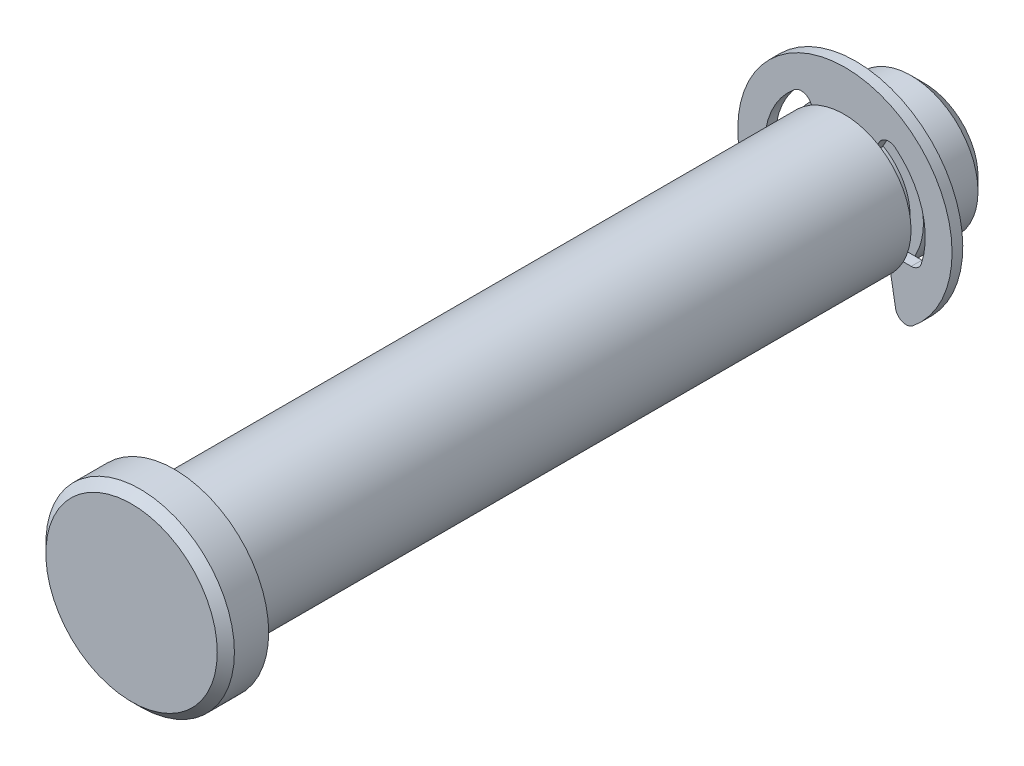
SolidWorks part; units mm, degrees
ref_plane "Front" through (0, 0, 0) normal (0, 0, 1) x (1, 0, 0)
ref_plane "Top" through (0, 0, 0) normal (0, 1, 0) x (1, 0, 0)
ref_plane "Right" through (0, 0, 0) normal (1, 0, 0) x (0, 0, -1)
sketch "Sketch2" plane through (0, 0, 0) normal (0, 0, 1) x (1, 0, 0)
  circle A0 centre (0, 0) radius 3.9688
  point P3 (0, 3.9688)
  point P4 (0, -3.9688)
  dimension "dia" = 7.9375
extrude "Extrude1" add sketch "Sketch2" along normal mid plane 44.45
sketch "Sketch3" plane through (0, 0, 0) normal (1, 0, 0) x (0, 0, -1)
  line L0 (22.225, 3.9688) -> (-22.225, 3.9688) construction
  line L1 (17.4625, 3.9688) -> (18.1991, 3.9688)
  line L2 (17.4625, 3.9688) -> (17.4625, 3.175)
  line L3 (17.4625, 3.175) -> (18.1991, 3.175)
  line L4 (18.1991, 3.9688) -> (18.1991, 3.175)
  line L5 (-22.225, 3.9688) -> (-22.225, -3.9688) construction
  line L10 (18.1991, 3.175) -> (18.1991, -3.175) construction
  point P11 (18.1991, 0)
  point P14 (17.8308, 3.9688)
  dimension "groove wd" = 0.7366
  dimension "groove dia" = 6.35
  dimension "usable lg" = 39.6875
revolve "Cut-Revolve1" cut sketch "Sketch3" angle 360 about axis through (0, 0, 22.225) along (0, 0, -1)
sketch "Sketch8" plane through (0, 0, 22.225) normal (0, 0, 1) x (1, 0, 0)
  circle A0 centre (0, 0) radius 5.588
  dimension "head dia" = 11.176
extrude "Extrude6" add sketch "Sketch8" along normal blind 2.54
chamfer "Chamfer2" distance 0.508 angle 45 1 edges at (5.588, 0, 24.765)
ref_plane "Plane1" through (0, 0, -17.8308) normal (0, 0, 1) x (1, 0, 0)
sketch "Sketch4" plane through (0, 0, -17.8308) normal (0, 0, 1) x (1, 0, 0)
  line L0 (0, 3.175) -> (0, -3.175) construction
  circle A0 centre (0, 0) radius 6.35
  circle A1 centre (0, 0) radius 3.175
  dimension "ring dia" = 12.7
extrude "Extrude2" add sketch "Sketch4" along normal mid plane 0.635 separate body
sketch "Sketch5" plane through (0, 0, 0) normal (0, 0, 1) x (1, 0, 0)
  line L0 (0, 6.35) -> (0, 3.175) construction
  line L1 (-2.3813, 4.1244) -> (0, 0)
  line L2 (-4.3649, -1.905) -> (-2.54, -1.905)
  line L3 (0, 0) -> (2.3813, 4.1244)
  line L4 (-2.54, -1.905) -> (-3.1739, -5.4999)
  line L5 (2.54, -1.905) -> (3.1739, -5.4999)
  line L6 (2.54, -1.905) -> (4.3649, -1.905)
  arc A0 (-2.3813, 4.1244) -> (-4.3649, -1.905) centre (0, 0) ccw
  circle A1 centre (0, 0) radius 6.35 construction
  circle A2 centre (0, 0) radius 3.175 construction
  arc A3 (4.3649, -1.905) -> (2.3813, 4.1244) centre (0, 0) ccw
  arc A4 (-3.1739, -5.4999) -> (3.1739, -5.4999) centre (0, 0) ccw
  circle A5 centre (0, 0) radius 3.175 construction
  point P10 (0, 4.7625)
  dimension "D1" = 30
  dimension "D2" = 10
  dimension "D3" = 1.905
extrude "Extrude4" cut sketch "Sketch5" against normal through all
sketch "Sketch6" plane through (0, 0, -17.5133) normal (0, 0, 1) x (1, 0, 0)
  line L0 (-1.5875, 2.7496) -> (1.5875, 2.7496)
  circle A0 centre (0, 0) radius 3.175 construction
  arc A1 (1.5875, 2.7496) -> (-1.5875, 2.7496) centre (0, 0) ccw
extrude "Extrude5" add sketch "Sketch6" against normal up to surface (0.635 mm away) up to face at (0, 0.8161, -18.1483)
fillet "Fillet1" radius 0.635 6 edges at (3.1739, -5.4999, -17.8308) (-3.1739, -5.4999, -17.8308) (4.3649, -1.905, -17.8308) (2.3813, 4.1244, -17.8308) (-2.3813, 4.1244, -17.8308) (-4.3649, -1.905, -17.8308)
chamfer "Chamfer1" distance 0.7937 angle 45 1 edges at (3.9688, 0, -22.225)
sketch "Sketch7" plane through (0, 0, 0) normal (1, 0, 0) x (0, 0, -1)
  line L0 (18.1483, 6.35) -> (17.5133, 6.35) construction
  line L1 (22.225, -3.9688) -> (22.225, 3.9688) construction
  line L2 (17.5133, -5.0511) -> (18.1483, -5.0511) construction
  line L3 (-24.765, 5.08) -> (-24.765, -5.08) construction
  point P0 (18.1991, -5.0511)
  point P1 (22.225, 3.9688)
  point P2 (-24.765, 5.588)
  point P6 (17.4625, 6.35)
  point P7 (22.225, -3.9688)
  point P12 (-22.225, 5.588)
  point P16 (17.4625, -5.0511)
equation "\"D1@Chamfer1\" = \"dia@Sketch2\" * .1"
equation "\"D1@Fillet1\" = \"ring dia@Sketch4\" * .05"
equation "\"D3@Sketch5\" = \"groove dia@Sketch3\" * .3"
equation "\"D1@Chamfer2\" = \"head ht@Extrude6\" * .2"
